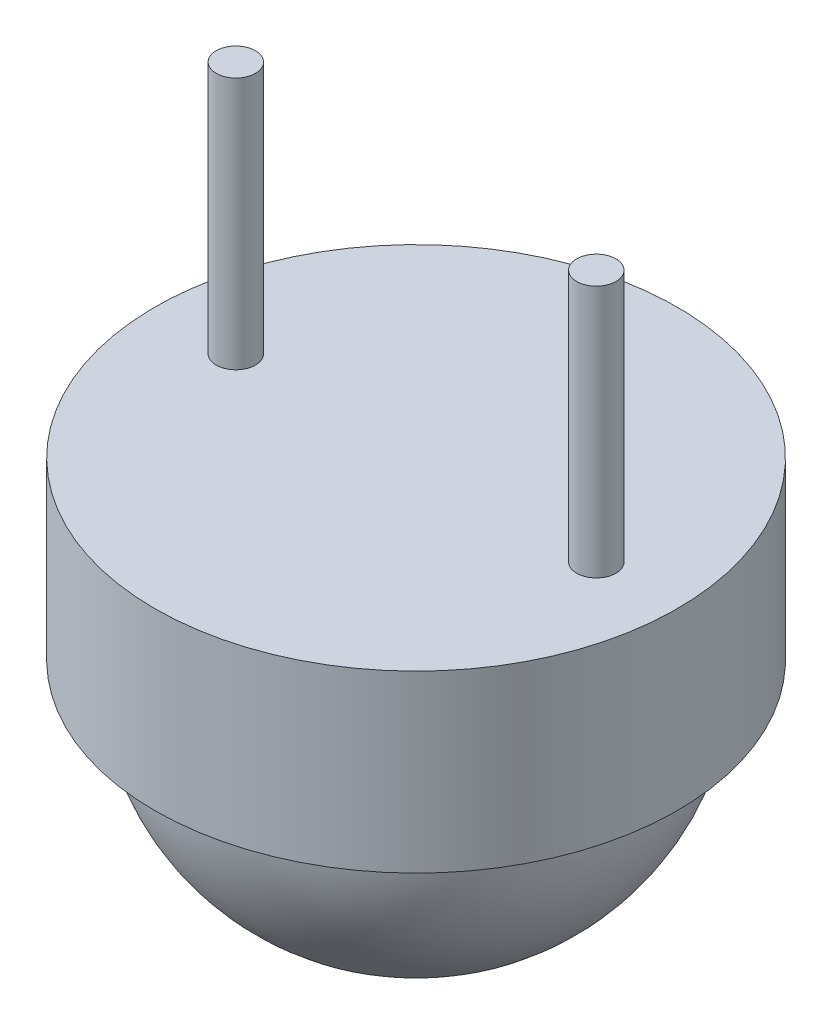
SolidWorks part; units mm, degrees
ref_plane "Front Plane" through (0, 0, 0) normal (0, 0, 1) x (1, 0, 0)
ref_plane "Top Plane" through (0, 0, 0) normal (0, 1, 0) x (1, 0, 0)
ref_plane "Right Plane" through (0, 0, 0) normal (1, 0, 0) x (0, 0, -1)
sketch "Sketch1" plane through (0, 0, 0) normal (0, 1, 0) x (1, 0, 0)
  circle A0 centre (0, 0) radius 11.05
  dimension "D1" = 22.1
extrude "Boss-Extrude1" add sketch "Sketch1" along normal blind 7.4
sketch "Sketch2" plane through (0, 0, 0) normal (1, 0, 0) x (0, 0, -1)
  line L0 (0, 0) -> (0, -9.525)
  line L1 (0, 0) -> (9.525, 0)
  line L2 (-11.05, 0) -> (11.05, 0) construction
  line L3 (0, 0) -> (0, 7.4) construction
  line L4 (11.05, 7.4) -> (-11.05, 7.4) construction
  arc A0 (0, -9.525) -> (9.525, 0) centre (0, 0) ccw
  dimension "D1" = 19.05
revolve "Revolve1" add sketch "Sketch2" angle 360 about L3
sketch "Sketch3" plane through (0, 7.4, 0) normal (0, 1, 0) x (1, 0, 0)
  line L0 (0, 0) -> (7.625, 0) construction
  circle A0 centre (7.625, 0) radius 0.83
  dimension "D2" = 1.66
  dimension "D1" = 7.625
extrude "Boss-Extrude2" add sketch "Sketch3" along normal blind 10.69
mirror "Mirror1" about plane through (0, 0, 0) normal (1, 0, 0) of "Boss-Extrude2"
